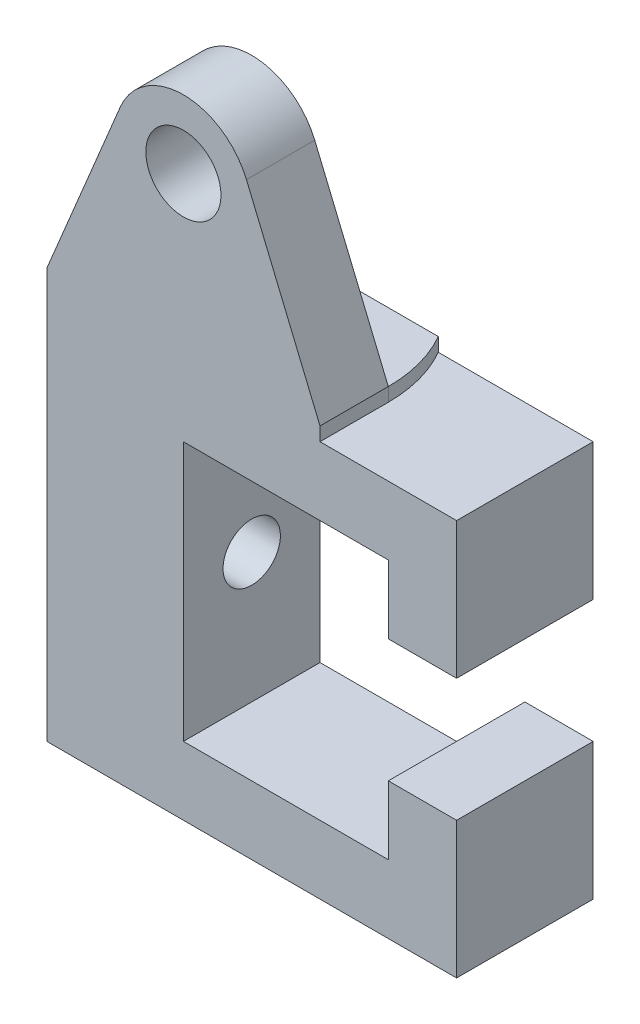
SolidWorks part; units mm, degrees
ref_plane "Front Plane" through (0, 0, 0) normal (0, 0, 1) x (1, 0, 0)
ref_plane "Top Plane" through (0, 0, 0) normal (0, 1, 0) x (1, 0, 0)
ref_plane "Right Plane" through (0, 0, 0) normal (1, 0, 0) x (0, 0, -1)
sketch "Sketch1" plane through (0, 0, 0) normal (0, 0, 1) x (1, 0, 0)
  line L0 (0, 0) -> (0, -23031.2068) construction
  line L1 (0, 0) -> (23031.2068, 0) construction
  line L2 (15, 5) -> (15, 0)
  line L3 (15, 0) -> (0, 0)
  line L4 (0, 0) -> (0, 19)
  line L5 (0, 19) -> (15, 19)
  line L6 (15, 19) -> (15, 14)
  line L7 (15, 14) -> (20, 14)
  line L8 (20, 14) -> (20, 24)
  line L9 (20, 24) -> (-10, 24)
  line L10 (-10, 24) -> (-10, -5)
  line L11 (-10, -5) -> (20, -5)
  line L12 (20, -5) -> (20, 5)
  line L13 (20, 5) -> (15, 5)
  dimension "D1" = 19
  dimension "D2" = 15
  dimension "D3" = 15
  dimension "D4" = 5
  dimension "D5" = 5
  dimension "D6" = 5
  dimension "D7" = 5
  dimension "D8" = 5
  dimension "D9" = 10
extrude "Boss-Extrude1" add sketch "Sketch1" along normal mid plane 10
sketch "Sketch2" plane through (-10, 0, 0) normal (-1, 0, 0) x (0, 0, 1)
  line L0 (0, 24) -> (0, -49976) construction
  line L1 (5, 24) -> (-5, 24) construction
  line L2 (-5, 9.5) -> (49995, 9.5) construction
  line L3 (-5, 24) -> (-5, -5) construction
  circle A0 centre (0, 9.5) radius 2.1
  point P4 (0, 24)
  point P9 (-5, 9.5)
  point P12 (0, 0)
  dimension "D1" = 4.2
extrude "Cut-Extrude1" cut sketch "Sketch2" against normal blind 10
sketch "Sketch3" plane through (0, 24, 0) normal (0, 1, 0) x (1, 0, 0)
  line L0 (0, -5) -> (0, 5) construction
  line L1 (0, -5) -> (0, 5) construction
  circle A0 centre (0, 0) radius 10
  dimension "D1" = 20
extrude "Boss-Extrude2" add sketch "Sketch3" along normal blind 1
sketch "Sketch4" plane through (0, 0, 0) normal (0, 0, 1) x (1, 0, 0)
  line L0 (10, 25) -> (-10, 25) construction
  line L1 (10, 25) -> (-10, 25)
  line L2 (0, 29) -> (0, 50029) construction
  line L3 (-10, 25) -> (-4.6154, 37.9231)
  line L4 (10, 25) -> (4.6154, 37.9231)
  circle A0 centre (0, 36) radius 2.75
  circle A1 centre (0, 36) radius 10 construction
  arc A3 (4.6154, 37.9231) -> (-4.6154, 37.9231) centre (0, 36) ccw
  point P4 (0, 25)
  point P9 (0, 0)
  dimension "D1" = 5.5
  dimension "D2" = 20
  dimension "D3" = 11
  dimension "D4" = 10
extrude "Boss-Extrude3" add sketch "Sketch4" along normal blind 5
sketch "Sketch5" plane through (0, -5, 0) normal (0, -1, 0) x (1, 0, 0)
  line L0 (-20, -15) -> (30, -15)
  line L1 (30, -15) -> (30, 15)
  line L2 (30, 15) -> (-20, 15)
  line L3 (-20, 15) -> (-20, -15)
  line L4 (-10, -5) -> (20, -5)
  line L5 (20, -5) -> (20, 5)
  line L6 (20, 5) -> (-10, 5)
  line L7 (-10, 5) -> (-10, -5)
  line L8 (-10, -5) -> (20, -5)
  line L9 (20, -5) -> (20, 5)
  line L10 (20, 5) -> (-10, 5)
  line L11 (-10, 5) -> (-10, -5)
  dimension "D1" = 0
  dimension "D2" = 10
extrude "Cut-Extrude2" cut sketch "Sketch5" against normal through all
sketch "Sketch6" plane through (0, 25, 0) normal (0, -1, 0) x (1, 0, 0)
  line L2 (10, 5) -> (8.6603, 5)
  line L3 (10, 0) -> (10, 5)
  line L4 (10, 5) -> (8.6603, 5)
  line L5 (10, 0) -> (10, 5)
  line L6 (-10, 5) -> (-10, 0)
  line L7 (-8.6603, 5) -> (-10, 5)
  line L8 (-10, 5) -> (-10, 0)
  line L9 (-8.6603, 5) -> (-10, 5)
  arc A1 (10, 0) -> (8.6603, 5) centre (0, 0) ccw
  arc A2 (10, 0) -> (8.6603, 5) centre (0, 0) ccw
  arc A3 (-8.6603, 5) -> (-10, 0) centre (0, 0) ccw
  arc A4 (-8.6603, 5) -> (-10, 0) centre (0, 0) ccw
  dimension "D1" = 0
  dimension "D2" = 0
extrude "Boss-Extrude4" add sketch "Sketch6" along normal blind 1
